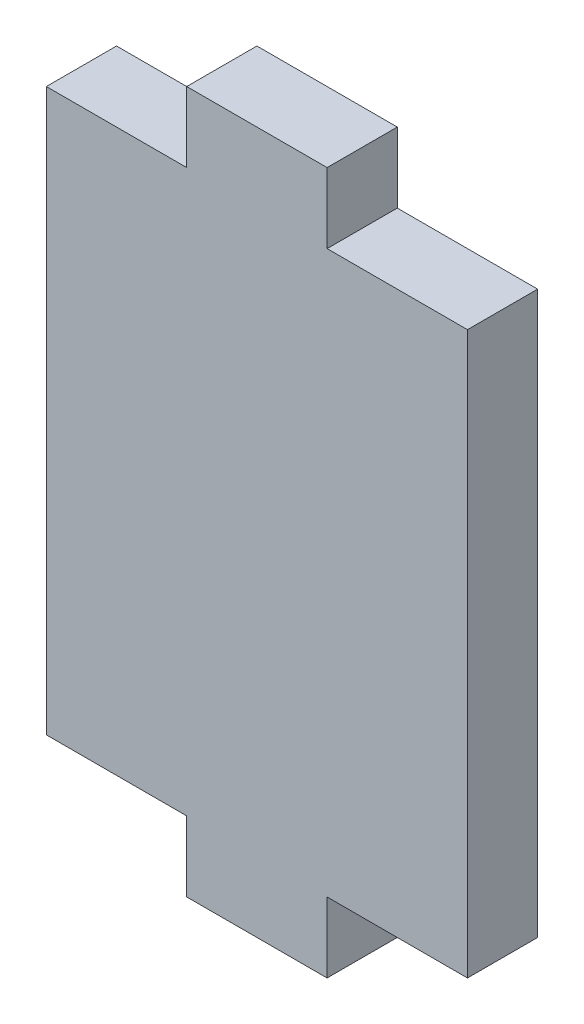
SolidWorks part; units mm, degrees
ref_plane "Front Plane" through (0, 0, 0) normal (0, 0, 1) x (1, 0, 0)
ref_plane "Top Plane" through (0, 0, 0) normal (0, 1, 0) x (1, 0, 0)
ref_plane "Right Plane" through (0, 0, 0) normal (1, 0, 0) x (0, 0, -1)
sketch "Sketch1" plane through (0, 0, 0) normal (0, 0, 1) x (1, 0, 0)
  line L0 (5, 20) -> (15, 20)
  line L1 (-15, -20) -> (-5, -20)
  line L2 (-15, -20) -> (-15, 20)
  line L3 (-15, 20) -> (-5, 20)
  line L4 (15, -20) -> (15, 20)
  line L5 (-15, -20) -> (15, 20) construction
  line L6 (-15, 20) -> (15, -20) construction
  line L8 (-5, 20) -> (-5, 25)
  line L9 (-5, 25) -> (5, 25)
  line L10 (5, 20) -> (5, 25)
  line L12 (-5, -20) -> (-5, -25)
  line L13 (-5, -25) -> (5, -25)
  line L14 (5, -20) -> (5, -25)
  line L15 (5, -20) -> (15, -20)
  point P0 (0, 0)
  dimension "D1" = 30
  dimension "D2" = 40
  dimension "D3" = 10
  dimension "D4" = 5
  dimension "D5" = 5
  dimension "D6" = 5
  dimension "D7" = 10
  dimension "D8" = 10
extrude "Boss-Extrude1" add sketch "Sketch1" along normal blind 5 contours L1 L12 L13 L14 L15 L4 L0 L10 L9 L8 L3 L2
